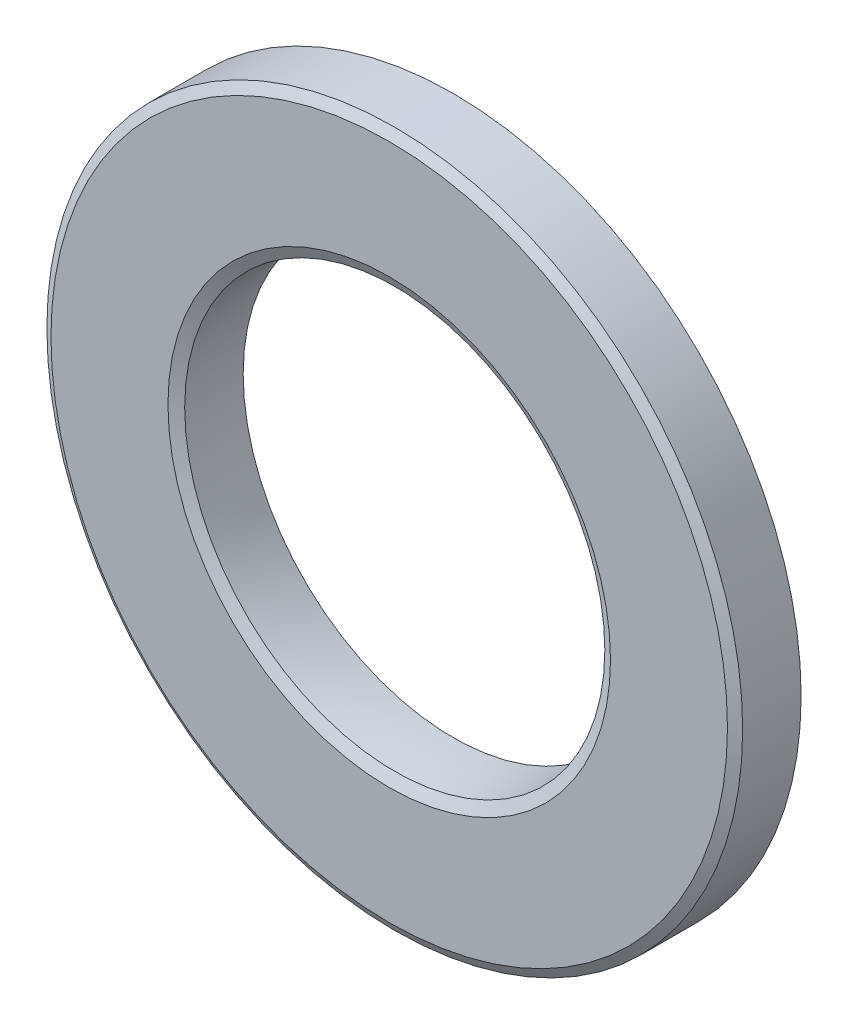
SolidWorks part; units mm, degrees
other "Imported1" parameters "D1"=0.254
material "Leaded Commercial Bronze"
ref_plane "Front Plane" through (0, 0, 0) normal (0, 0, 1) x (1, 0, 0)
ref_plane "Top Plane" through (0, 0, 0) normal (0, 1, 0) x (1, 0, 0)
ref_plane "Right Plane" through (0, 0, 0) normal (1, 0, 0) x (0, 0, -1)
sketch "Sketch1" plane through (0, 0, 0) normal (0, 0, 1) x (1, 0, 0)
  line L0 (-15.875, 0) -> (15.875, 0) construction
  line L1 (-9.5504, 0) -> (9.5504, 0) construction
  circle A0 centre (0, 0) radius 9.5504 construction
  circle A1 centre (0, 0) radius 15.875 construction
  point P8 (0, 0)
  point P9 (0, 15.875)
  point P11 (9.5504, 0)
  dimension "ID" = 19.1008
  dimension "OD" = 31.75
sketch "Sketch2" plane through (0, 0, 0) normal (1, 0, 0) x (0, 0, -1)
  line L0 (-1.5875, 15.875) -> (1.5875, 15.875) construction
  point P2 (0, 15.875)
  dimension "Thickness" = 3.175
sketch "Sketch3" plane through (0, 0, 0) normal (0, 0, 1) x (1, 0, 0)
  circle A0 centre (0, 0) radius 9.5504
  circle A1 centre (0, 0) radius 15.875
extrude "Boss-Extrude1" add sketch "Sketch3" along normal up to vertex (1.5875 mm away) and the other way up to vertex (1.5875 mm away) up to point (0, 15.875, 1.5875) other way up to point (0, 15.875, -1.5875)
chamfer "Chamfer1" distance 0.254 angle 60 2 edges at (15.875, 0, -1.5875) (15.875, 0, 1.5875)
sketch "Sketch4" plane through (0, 0, 0) normal (1, 0, 0) x (0, 0, -1)
  line L3 (-1.5875, 9.4996) -> (-1.5875, 9.6012)
  line L4 (-1.5875, 9.4996) -> (1.5875, 9.4996)
  line L5 (1.5875, 9.4996) -> (1.5875, 9.6012)
  line L6 (-1.5875, 0) -> (1.5875, 0) construction
  arc A0 (-1.5875, 9.6012) -> (1.5875, 9.6012) centre (0, 34.3805) ccw
  point P0 (0, 9.5504)
  point P9 (-1.5875, 9.5504)
  point P13 (0, 0)
  dimension "D1" = 0.0508
revolve "Cut-Revolve1" cut sketch "Sketch4" angle 360 about L6
chamfer "Chamfer2" distance 0.254 angle 60 2 edges at (0, -9.6012, -1.5875) (0, -9.6012, 1.5875)
equation "\"D1@Chamfer2\"=\"D1@Chamfer1\""
